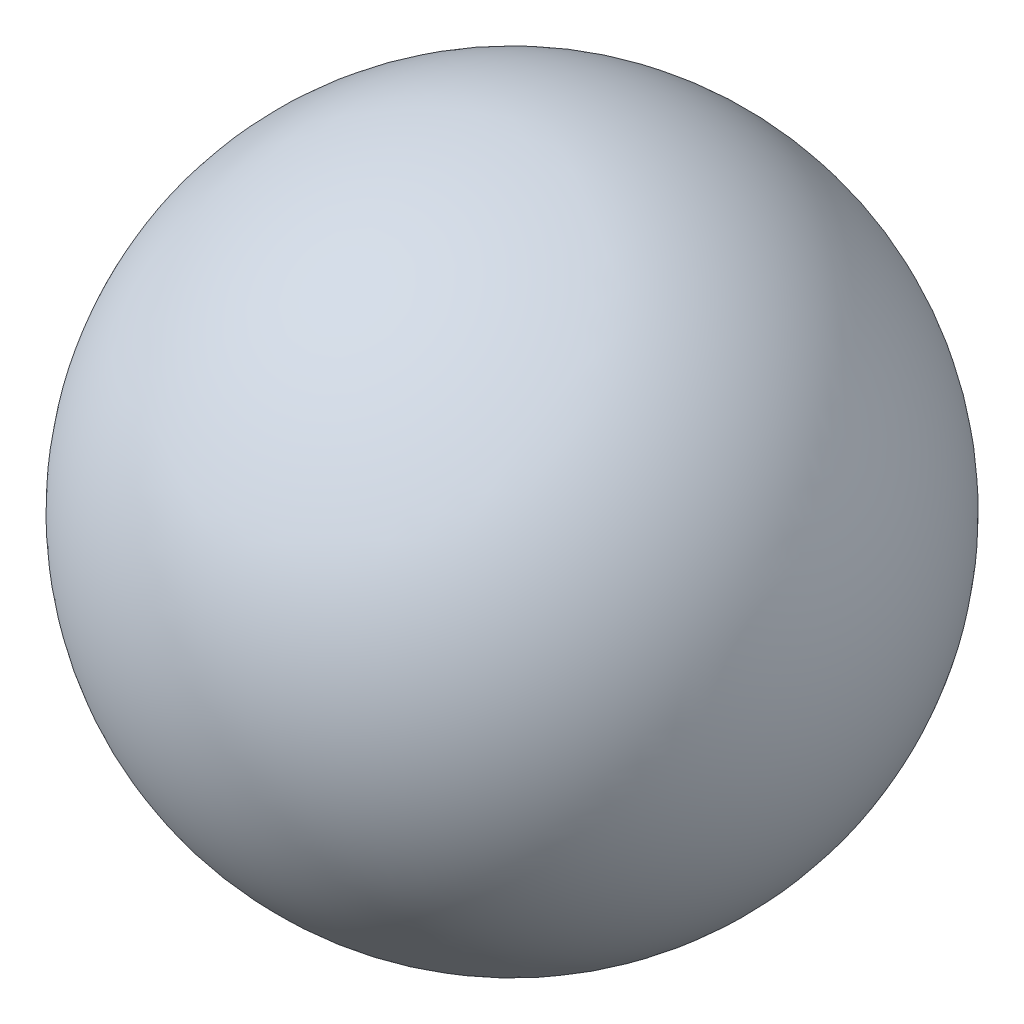
SolidWorks part; units mm, degrees
ref_plane "Front Plane" through (0, 0, 0) normal (0, 0, 1) x (1, 0, 0)
ref_plane "Top Plane" through (0, 0, 0) normal (0, 1, 0) x (1, 0, 0)
ref_plane "Right Plane" through (0, 0, 0) normal (1, 0, 0) x (0, 0, -1)
sketch "Sketch1" plane through (0, 0, 0) normal (0, 0, 1) x (1, 0, 0)
  line L0 (-12, 0) -> (12, 0) construction
  line L1 (12, 0) -> (-12, 0) construction
  line L2 (12, 0) -> (-12, 0)
  arc A0 (12, 0) -> (-12, 0) centre (0, 0) ccw
  dimension "D2" = 12
  dimension "D1" = 24
revolve "Revolve2" add sketch "Sketch1" angle 360 about L2
